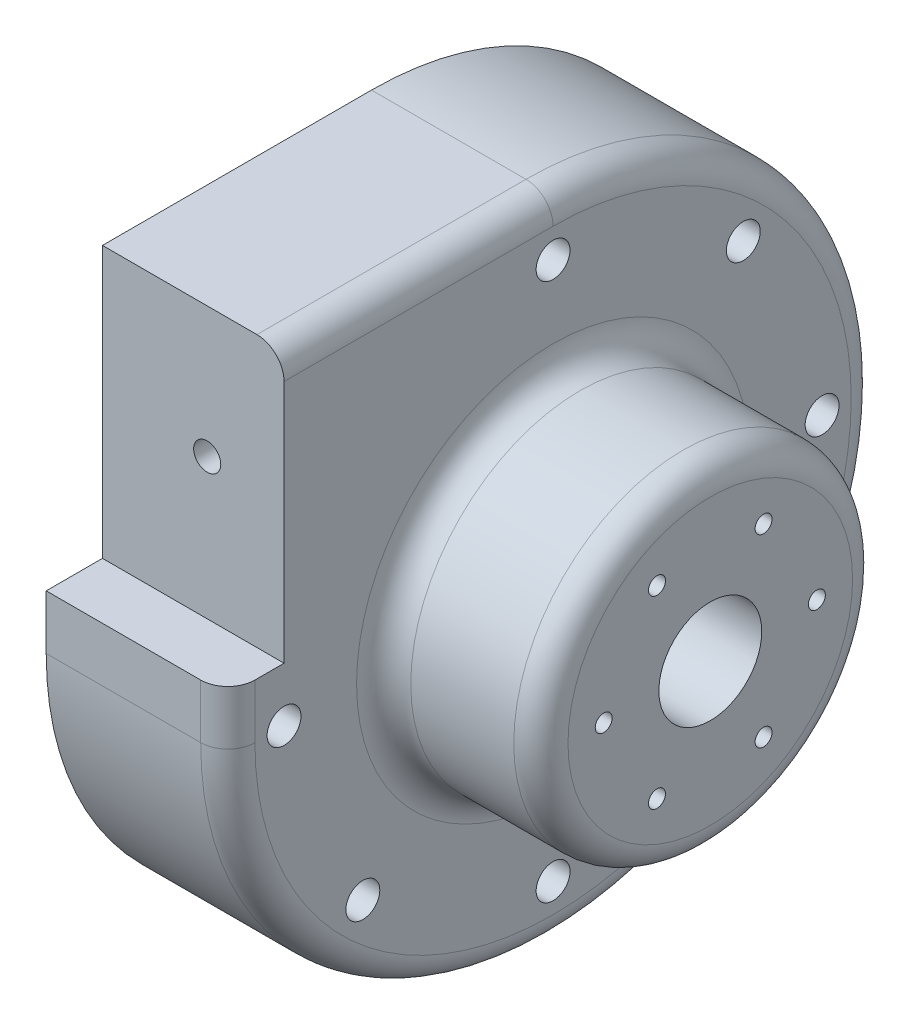
SolidWorks part; units mm, degrees
ref_plane "Front Plane" through (0, 0, 0) normal (0, 0, 1) x (1, 0, 0)
ref_plane "Top Plane" through (0, 0, 0) normal (0, 1, 0) x (1, 0, 0)
ref_plane "Right Plane" through (0, 0, 0) normal (1, 0, 0) x (0, 0, -1)
sketch "Sketch1" plane through (0, 0, 0) normal (1, 0, 0) x (0, 0, -1)
  line L0 (-60.96, 0) -> (-60.96, 60.96)
  line L1 (-60.96, 60.96) -> (0, 60.96)
  arc A1 (-60.96, 0) -> (0, 60.96) centre (0, 0) ccw
extrude "Housing 2" add sketch "Sketch1" along normal blind 44.45 contours L0 L1 A1
sketch "Sketch2" plane through (0, 0, 0) normal (-1, 0, 0) x (0, 0, 1)
  circle A0 centre (0, 0) radius 39.878
extrude "Impeller Cut" cut sketch "Sketch2" against normal blind 22.4028
sketch "Sketch3" plane through (0, 0, 0) normal (0, 0, 1) x (1, 0, 0)
  line L2 (29.6028, 9.6415) -> (22.4028, 39.878)
  line L3 (29.6028, 9.6415) -> (29.6028, 0)
  line L4 (44.45, 0) -> (0, 0) construction
  line L7 (22.4028, 39.878) -> (22.225, 0)
  line L8 (22.225, 0) -> (29.6028, 0)
revolve "Impeller Angle Cut" cut sketch "Sketch3" angle 360 about L8
sketch "Sketch4" plane through (29.6028, 0, 0) normal (-1, 0, 0) x (0, 0, 1)
  circle A0 centre (0, 0) radius 9.6415
extrude "Inlet Cut" cut sketch "Sketch4" against normal blind 19.8628
sketch "Sketch5" plane through (44.45, 0, 0) normal (1, 0, 0) x (0, 0, -1)
  circle A1 centre (0, 19.05) radius 1.5875
extrude "Inlet Fastener Bore" [suppressed] cut sketch "Sketch5" against normal blind 6.35
pattern_circular "Inlet Fastener Pattern" [suppressed] count 6 over 360
sketch "Sketch6" plane through (44.45, 0, 0) normal (1, 0, 0) x (0, 0, -1)
  circle A2 centre (50.419, 0) radius 3.175
extrude "Fastener Bore" cut sketch "Sketch6" against normal blind 116.84
pattern_circular "Fastener Pattern" count 8 over 360 about axis through (0, 0, 0) along (1, 0, 0) skipping 5 of "Fastener Bore"
sketch "Sketch7" plane through (44.45, 0, 0) normal (1, 0, 0) x (0, 0, -1)
  circle A0 centre (0, 0) radius 31.75
  circle A1 centre (0, 0) radius 100.1143
extrude "Mass Reduction Cut" cut sketch "Sketch7" against normal blind 10.414
fillet "Fillet3" radius 5.08 1 edges at (34.036, 0, -31.75)
sketch "Sketch8" plane through (0, 0, 60.96) normal (0, 0, 1) x (1, 0, 0)
  line L0 (34.036, 0) -> (34.036, 60.96) construction
  line L1 (0, 60.96) -> (34.036, 60.96)
  line L2 (0, 60.96) -> (0, 10.1635)
  line L3 (0, 10.1635) -> (34.036, 10.1635)
  line L4 (34.036, 60.96) -> (34.036, 10.1635)
extrude "Discharge Cut" cut sketch "Sketch8" against normal blind 10.541
fillet "Fillet4" radius 5.08 3 edges at (34.036, 5.0817, 60.96) (34.036, 60.96, 25.2095) (34.036, -43.1052, -43.1052)
sketch "Sketch9" plane through (0, 0, 50.419) normal (0, 0, 1) x (1, 0, 0)
  circle A0 centre (19.6343, 36.5011) radius 2.54
extrude "Discharge Bore" cut sketch "Sketch9" against normal blind 50.038
sketch "Sketch11" plane through (44.45, 0, 0) normal (1, 0, 0) x (0, 0, -1)
  circle A0 centre (0, 0) radius 31.75
  circle A1 centre (0, 0) radius 9.6415
extrude "Boss-Extrude1" add sketch "Sketch11" along normal blind 19.05
sketch "Sketch12" plane through (63.5, 0, 0) normal (1, 0, 0) x (0, 0, -1)
  circle A0 centre (19.976, 0) radius 1.5875
extrude "Cut-Extrude1" cut sketch "Sketch12" against normal blind 19.05
pattern_circular "CirPattern1" count 6 over 360 about axis through (0, 0, 0) along (1, 0, 0) of "Cut-Extrude1"
fillet "Fillet6" radius 5.08 1 edges at (63.5, 0, -31.75)
